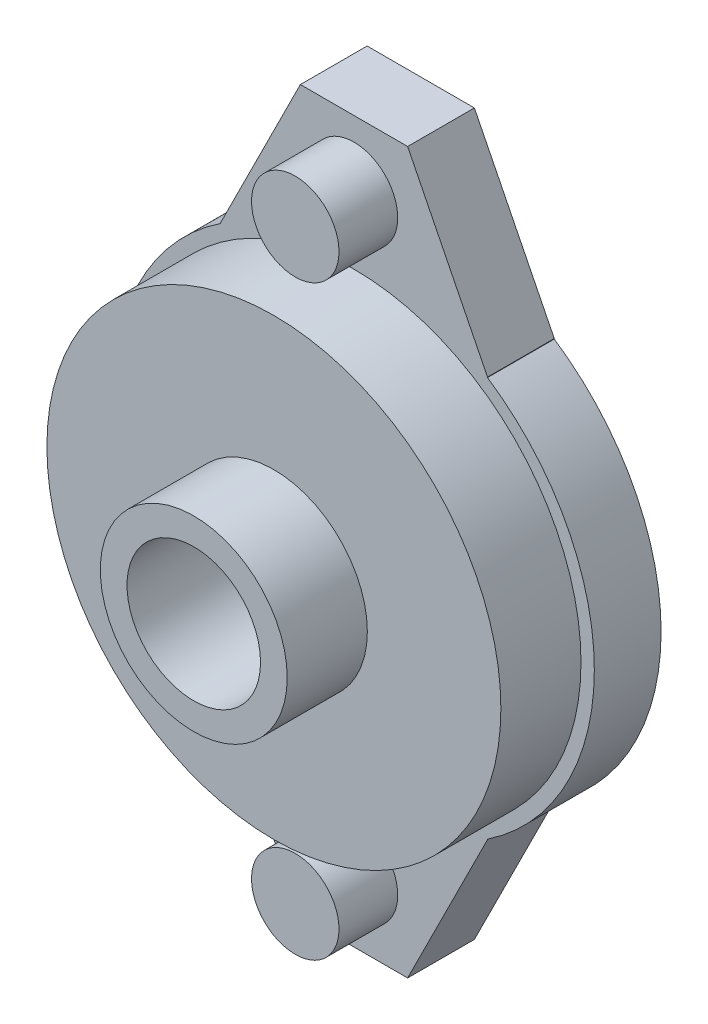
SolidWorks part; units mm, degrees
ref_plane "정면" through (0, 0, 0) normal (0, 0, 1) x (1, 0, 0)
ref_plane "윗면" through (0, 0, 0) normal (0, 1, 0) x (1, 0, 0)
ref_plane "우측면" through (0, 0, 0) normal (1, 0, 0) x (0, 0, -1)
sketch "스케치1" plane through (0, 0, 0) normal (0, 0, 1) x (1, 0, 0)
  circle A0 centre (0, 0) radius 17
  dimension "D1" = 34
extrude "보스-돌출1" add sketch "스케치1" along normal blind 6
sketch "스케치2" plane through (0, 0, 6) normal (0, 0, 1) x (1, 0, 0)
  circle A0 centre (0, 0) radius 7
  dimension "D1" = 14
extrude "보스-돌출2" add sketch "스케치2" along normal blind 6
sketch "스케치3" plane through (0, 0, 0) normal (0, 0, -1) x (-1, 0, 0)
  circle A0 centre (0, 0) radius 18
  dimension "D1" = 36
extrude "보스-돌출3" add sketch "스케치3" along normal blind 5
sketch "스케치8" plane through (0, 0, -5) normal (0, 0, -1) x (-1, 0, 0)
  line L0 (-10, 14.9666) -> (10, 14.9666) construction
  line L1 (-10, 14.9666) -> (-10, 26.9666)
  line L2 (-10, 26.9666) -> (10, 26.9666)
  line L3 (10, 26.9666) -> (10, 14.9666)
  arc A0 (-10, 14.9666) -> (10, 14.9666) centre (0, 0) cw
  circle A1 centre (0, 0) radius 18 construction
  dimension "D1" = 20
  dimension "D2" = 12
extrude "보스-돌출6" add sketch "스케치8" against normal blind 5
sketch "스케치5" plane through (0, 0, 0) normal (0, 0, 1) x (1, 0, 0)
  line L0 (-10, 27) -> (-10, 15)
  line L3 (-10, 15) -> (-4, 27)
  line L5 (-4, 27) -> (-10, 27)
  line L6 (0, -9.35) -> (0, 9.35) construction
  line L7 (4, 27) -> (10, 27)
  line L8 (10, 15) -> (4, 27)
  line L9 (10, 27) -> (10, 15)
  dimension "D1" = 8
extrude "컷-돌출1" cut sketch "스케치5" against normal blind 8
sketch "스케치6" plane through (0, 0, 0) normal (0, 0, 1) x (1, 0, 0)
  line L1 (-4.0167, 26.9666) -> (4.0167, 26.9666) construction
  circle A0 centre (0, 21.9666) radius 3.275
  dimension "D2" = 6.55
  dimension "D1" = 5
extrude "보스-돌출5" add sketch "스케치6" along normal blind 4.4
mirror "대칭 복사6" about plane through (0, 0, 0) normal (0, 1, 0) of "보스-돌출5", "컷-돌출1", "보스-돌출6"
sketch "스케치9" plane through (0, 0, 12) normal (0, 0, 1) x (1, 0, 0)
  circle A0 centre (0, 0) radius 5
extrude "컷-돌출3" cut sketch "스케치9" against normal through all
sketch "스케치10" plane through (0, 0, -5) normal (0, 0, -1) x (-1, 0, 0)
  circle A0 centre (0, 0) radius 8.6
  circle A1 centre (0, 0) radius 13.6
  arc A2 (-10, 14.9666) -> (-10, -14.9666) centre (0, 0) ccw construction
  dimension "D1" = 4.4
  dimension "D2" = 5
extrude "컷-돌출4" cut sketch "스케치10" against normal blind 3
